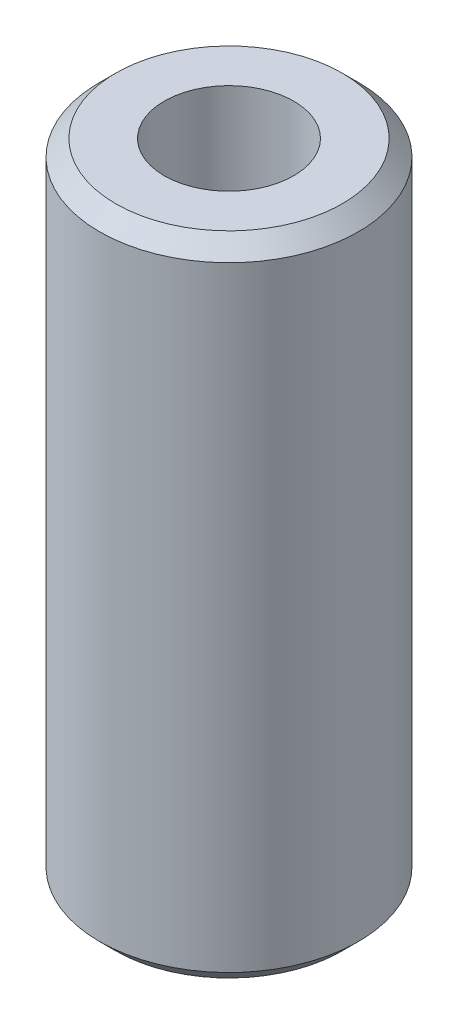
SolidWorks part; units mm, degrees
ref_plane "Front Plane" through (0, 0, 0) normal (0, 0, 1) x (1, 0, 0)
ref_plane "Top Plane" through (0, 0, 0) normal (0, 1, 0) x (1, 0, 0)
ref_plane "Right Plane" through (0, 0, 0) normal (1, 0, 0) x (0, 0, -1)
sketch "Sketch1" plane through (0, 0, 0) normal (0, 1, 0) x (1, 0, 0)
  circle A0 centre (0, 0) radius 2
  circle A1 centre (0, 0) radius 4
  dimension "D1" = 4
  dimension "D2" = 2
extrude "Boss-Extrude1" add sketch "Sketch1" along normal blind 20
chamfer "Chamfer1" distance 0.5 angle 45 2 edges at (0, 0, 4) (0, 20, 4)
